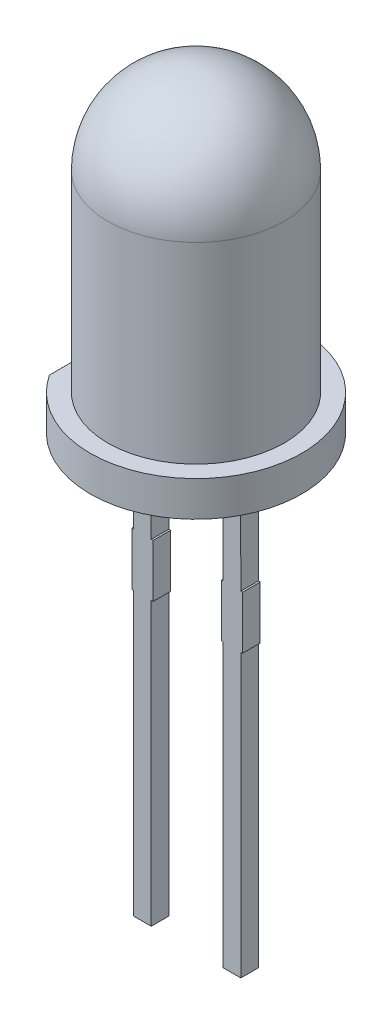
SolidWorks part; units mm, degrees
ref_plane "Front Plane" through (0, 0, 0) normal (0, 0, 1) x (1, 0, 0)
ref_plane "Top Plane" through (0, 0, 0) normal (0, 1, 0) x (1, 0, 0)
ref_plane "Right Plane" through (0, 0, 0) normal (1, 0, 0) x (0, 0, -1)
sketch "Sketch1" plane through (0, 0, 0) normal (0, 1, 0) x (1, 0, 0)
  line L2 (-2.5, 0) -> (-2.5, 1.6583)
  line L3 (-2.5, 0) -> (-2.5, -1.6583)
  arc A0 (-2.5, -1.6583) -> (-2.5, 1.6583) centre (0, 0) ccw
  point P7 (2.8689, 0.8771)
  dimension "D1" = 6
extrude "Boss-Extrude1" add sketch "Sketch1" along normal blind 1
sketch "Sketch3" plane through (0, 0, 0) normal (1, 0, 0) x (0, 0, -1)
  line L0 (0, 0.5261) -> (0, 8.9449)
  line L1 (0, -0.0551) -> (-7.4501, -0.0551) construction
  line L2 (-2.5, 6.4449) -> (-2.5, 0.5261)
  line L4 (0, 0.5261) -> (-2.5, 0.5261)
  arc A0 (0, 8.9449) -> (-2.5, 6.4449) centre (0, 6.4449) ccw
  point P3 (0, 6.4449)
  dimension "D2" = 2.5
  dimension "D1" = 9
revolve "Revolve1" add sketch "Sketch3" angle 360 about L0
sketch "Sketch4" plane through (0, 0, 0) normal (0, 0, 1) x (1, 0, 0)
  line L0 (0, 8.9449) -> (0, 0) construction
  line L1 (-2.5, 4.4796) -> (3.2224, 4.4796) construction
  line L2 (-2.5, 6.4449) -> (-2.5, 1) construction
  line L3 (-1.27, -7.747) -> (-1.27, 9.0925) construction
  line L4 (-1.02, -9.137) -> (-1.02, 5.2073) construction
  line L5 (-1.02, -3) -> (-1.02, 1.7015)
  line L6 (-1.02, 1.7015) -> (-0.5369, 1.7015)
  line L7 (-0.5369, 1.7015) -> (0.8878, 4.4796)
  line L8 (0.8878, 4.4796) -> (-1.2657, 4.4796)
  line L9 (-1.2657, 4.4796) -> (-1.52, 4.228)
  line L10 (-1.52, 5.2073) -> (-1.52, -8.7128) construction
  line L11 (-3.3286, 0) -> (4.0168, 0) construction
  line L12 (-1.52, 4.228) -> (-1.52, -3)
  line L13 (1.52, 5.2073) -> (1.52, -8.7128) construction
  line L14 (1.27, -7.747) -> (1.27, 9.0925) construction
  line L15 (1.02, -9.137) -> (1.02, 5.2073) construction
  line L16 (1.02, -3) -> (1.02, 1.7015)
  line L17 (1.02, 1.7015) -> (-0.1915, 1.7015)
  line L18 (1.27, 4.4796) -> (-0.1915, 1.7015)
  line L19 (1.5049, 4.4796) -> (1.52, -3)
  line L20 (1.5049, 4.4796) -> (1.27, 4.4796)
  line L21 (-2.1607, 0) -> (-2.1607, -3) construction
  line L22 (-1.52, -3) -> (-1.57, -3)
  line L23 (-1.57, -3) -> (-1.57, -4.5)
  line L24 (-1.57, -4.5) -> (-1.52, -4.5)
  line L25 (-1.52, -4.5) -> (-1.52, -12.5)
  line L26 (-1.52, -12.5) -> (-1.02, -12.5)
  line L27 (-1.02, -3) -> (-0.97, -3)
  line L28 (-0.97, -4.5) -> (-1.02, -4.5)
  line L29 (-1.02, -4.5) -> (-1.02, -12.5)
  line L30 (-0.97, -3) -> (-0.97, -4.5)
  line L31 (0.97, -3) -> (0.97, -4.5)
  line L32 (1.02, -4.5) -> (1.02, -12.5)
  line L33 (0.97, -4.5) -> (1.02, -4.5)
  line L34 (1.02, -3) -> (0.97, -3)
  line L35 (1.52, -12.5) -> (1.02, -12.5)
  line L36 (1.52, -4.5) -> (1.52, -12.5)
  line L37 (1.57, -4.5) -> (1.52, -4.5)
  line L38 (1.57, -3) -> (1.57, -4.5)
  line L39 (1.52, -3) -> (1.57, -3)
  arc A0 (2.5, 6.4449) -> (-2.5, 6.4449) centre (0, 6.4449) ccw construction
  point P49 (-1.27, -12.5)
  point P57 (1.27, -12.5)
  dimension "D2" = 0.25
  dimension "D4" = 3
  dimension "D5" = 0.05
  dimension "D6" = 1.5
  dimension "D7" = 8
extrude "Boss-Extrude2" add sketch "Sketch4" along normal mid plane 0.5 separate body
sketch "Sketch6" plane through (0, 0, 0) normal (0, 0, 1) x (1, 0, 0)
  line L0 (0.1593, 6.1668) -> (0.1593, 2.9773) construction
  line L1 (0.1593, 4.5018) -> (0.9382, 4.5018)
  line L2 (0.9382, 4.5018) -> (0.1593, 2.9915)
  line L3 (0.1593, 4.5018) -> (0.1593, 2.9915)
revolve "Revolve2" add sketch "Sketch6" angle 360 about L0
sketch "Sketch9" plane through (0, 4.5018, 0) normal (0, 1, 0) x (1, 0, 0)
  circle A0 centre (0.1593, 0) radius 0.6
  dimension "D1" = 1.2
extrude "Cut-Extrude1" cut sketch "Sketch9" against normal blind 0.1
fillet "Fillet1" radius 0.05 1 edges at (-0.4407, 4.5018, 0)
